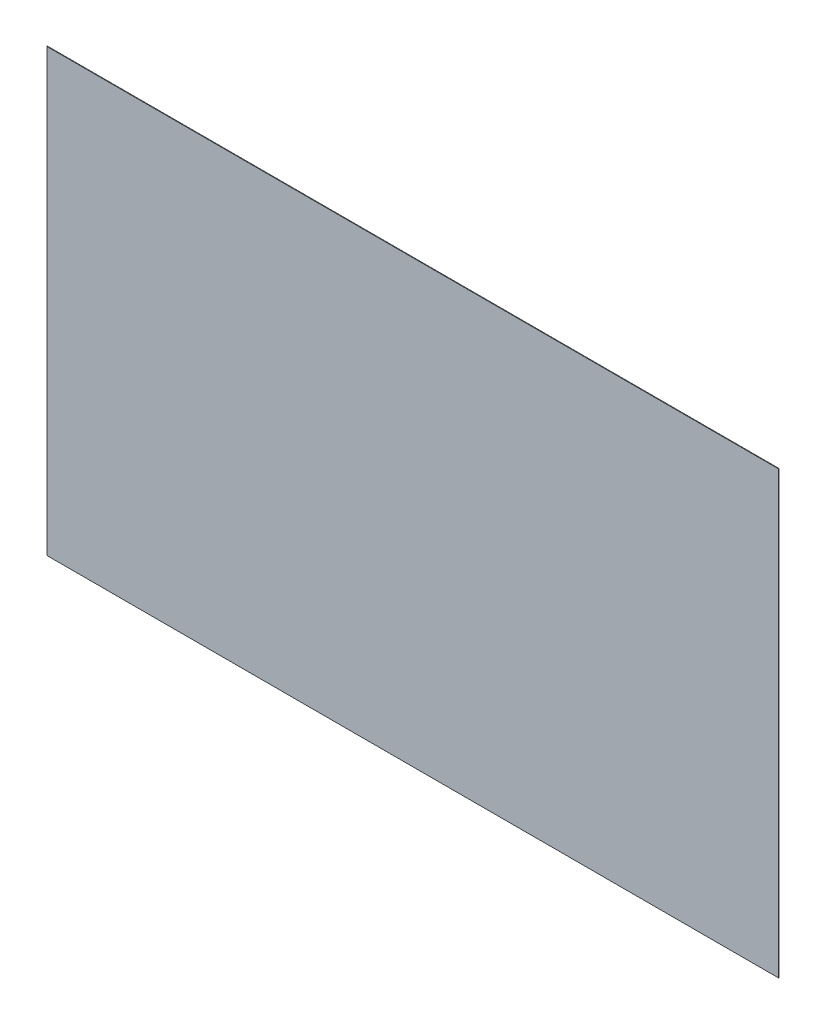
SolidWorks part; units mm, degrees
ref_plane "Front Plane" through (0, 0, 0) normal (0, 0, 1) x (1, 0, 0)
ref_plane "Top Plane" through (0, 0, 0) normal (0, 1, 0) x (1, 0, 0)
ref_plane "Right Plane" through (0, 0, 0) normal (1, 0, 0) x (0, 0, -1)
sketch "Sketch1" plane through (0, 0, 0) normal (0, 0, 1) x (1, 0, 0)
  line L0 (2500, 1506) -> (2500, 0)
  line L1 (2500, 1506) -> (0, 1506)
  line L2 (2500, 0) -> (0, 0)
  line L3 (0, 1506) -> (0, 0)
other "Pen Sketch1" parameters "D1"=69.7562, "D2"=44.2015
extrude "Boss-Extrude1" add sketch "Sketch1" along normal blind 2
